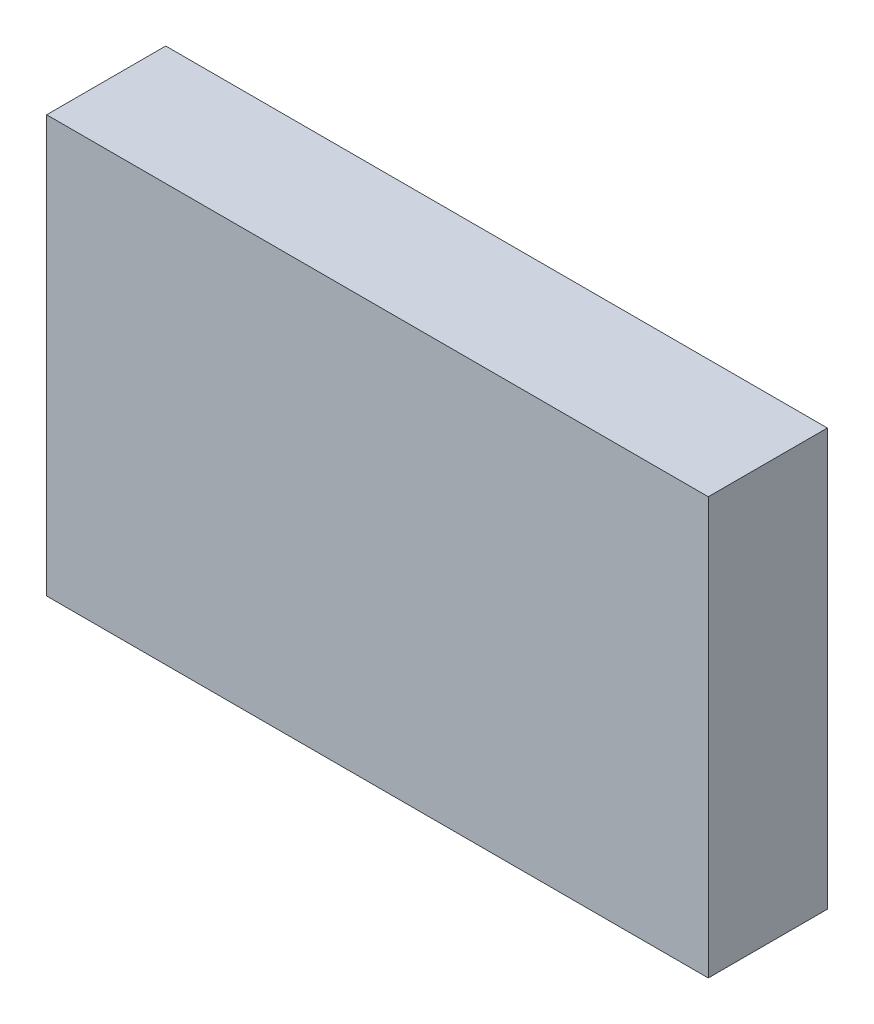
SolidWorks part; units mm, degrees
ref_plane "Front Plane" through (0, 0, 0) normal (0, 0, 1) x (1, 0, 0)
ref_plane "Top Plane" through (0, 0, 0) normal (0, 1, 0) x (1, 0, 0)
ref_plane "Right Plane" through (0, 0, 0) normal (1, 0, 0) x (0, 0, -1)
sketch "Sketch1" plane through (0, 0, 0) normal (0, 0, 1) x (1, 0, 0)
  line L0 (0, -0.6286) -> (0, 0.6286) construction
  line L1 (-3.175, 2) -> (3.175, 2)
  line L2 (-3.175, 2) -> (-3.175, -2)
  line L3 (-3.175, -2) -> (3.175, -2)
  line L4 (3.175, 2) -> (3.175, -2)
  line L5 (-3.175, 2) -> (3.175, -2) construction
  line L6 (-3.175, -2) -> (3.175, 2) construction
  line L7 (0.6286, 0) -> (-0.6286, 0) construction
  point P0 (0, 0)
  dimension "D1" = 4
  dimension "D2" = 6.35
extrude "Boss-Extrude1" add sketch "Sketch1" along normal blind 1.143
